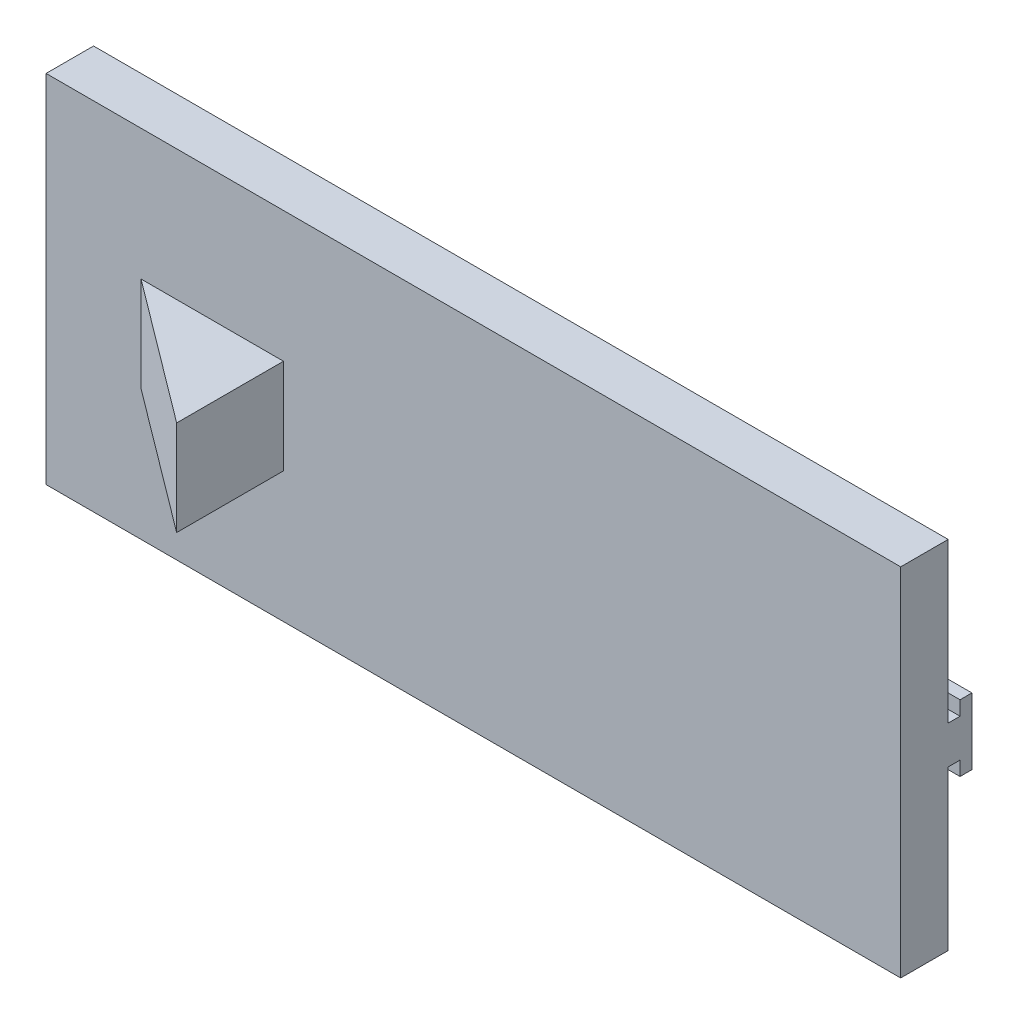
SolidWorks part; units mm, degrees
ref_plane "Front Plane" through (0, 0, 0) normal (0, 0, 1) x (1, 0, 0)
ref_plane "Top Plane" through (0, 0, 0) normal (0, 1, 0) x (1, 0, 0)
ref_plane "Right Plane" through (0, 0, 0) normal (1, 0, 0) x (0, 0, -1)
sketch "Sketch1" plane through (0, 0, 0) normal (0, 0, 1) x (1, 0, 0)
  line L1 (-228.6, -95.25) -> (228.6, -95.25)
  line L2 (-228.6, -95.25) -> (-228.6, 95.25)
  line L3 (-228.6, 95.25) -> (228.6, 95.25)
  line L4 (228.6, -95.25) -> (228.6, 95.25)
  line L5 (-228.6, -95.25) -> (228.6, 95.25) construction
  line L6 (-228.6, 95.25) -> (228.6, -95.25) construction
  point P0 (0, 0)
  dimension "D1" = 190.5
  dimension "D2" = 457.2
extrude "Boss-Extrude1" add sketch "Sketch1" along normal blind 25.4
sketch "Sketch2" plane through (0, 0, 0) normal (0, 0, -1) x (-1, 0, 0)
  line L0 (-228.6, -95.25) -> (-228.6, 95.25) construction
  line L1 (-228.6, 10.16) -> (228.6, 10.16)
  line L2 (-228.6, 10.16) -> (-228.6, -10.16)
  line L3 (-228.6, -10.16) -> (228.6, -10.16)
  line L4 (228.6, 10.16) -> (228.6, -10.16)
  line L5 (228.6, 95.25) -> (228.6, -95.25) construction
  point P9 (-228.6, 0)
  point P10 (-228.6, 0)
  dimension "D1" = 20.32
extrude "Boss-Extrude2" add sketch "Sketch2" along normal blind 12.7
sketch "Sketch3" plane through (0, 10.16, 0) normal (0, 1, 0) x (1, 0, 0)
  line L0 (228.6, 12.7) -> (228.6, 0) construction
  line L1 (-228.6, 12.7) -> (228.6, 12.7)
  line L2 (-228.6, 12.7) -> (-228.6, 6.35)
  line L3 (-228.6, 6.35) -> (228.6, 6.35)
  line L4 (228.6, 12.7) -> (228.6, 6.35)
extrude "Boss-Extrude3" add sketch "Sketch3" along normal blind 7.62 and the other way blind 27.94
sketch "Sketch5" plane through (0, 0, 0) normal (0, 1, 0) x (1, 0, 0)
  line L0 (-177.8, -25.4) -> (-101.6, -25.4)
  line L1 (-101.6, -25.4) -> (-101.6, -82.55)
  line L2 (-101.6, -82.55) -> (-177.8, -25.4)
  line L3 (228.6, -25.4) -> (-228.6, -25.4) construction
  point P2 (-101.6, -108.4788)
  dimension "D1" = 50.8
  dimension "D2" = 57.15
  dimension "D3" = 76.2
extrude "Boss-Extrude5" add sketch "Sketch5" along normal blind 25.4 and the other way blind 25.4
